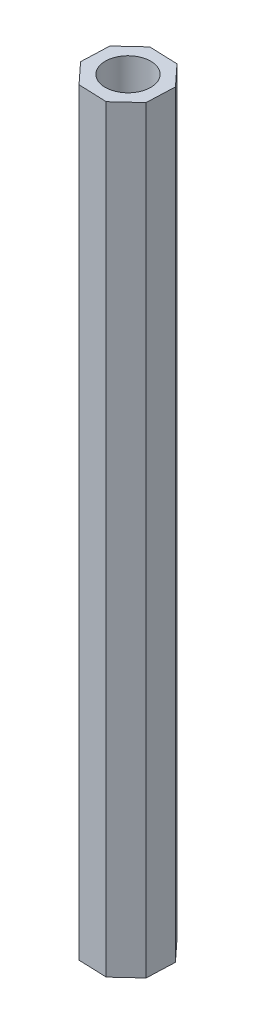
SolidWorks part; units mm, degrees
ref_plane "Front Plane" through (0, 0, 0) normal (0, 0, 1) x (1, 0, 0)
ref_plane "Top Plane" through (0, 0, 0) normal (0, 1, 0) x (1, 0, 0)
ref_plane "Right Plane" through (0, 0, 0) normal (1, 0, 0) x (0, 0, -1)
sketch "Sketch1" plane through (0, 0, 0) normal (0, 1, 0) x (1, 0, 0)
  line L1 (2.2842, 0.8447) -> (1.0179, 2.2125)
  line L2 (1.0179, 2.2125) -> (-0.8447, 2.2842)
  line L3 (-0.8447, 2.2842) -> (-2.2125, 1.0179)
  line L4 (-2.2125, 1.0179) -> (-2.2842, -0.8447)
  line L5 (-2.2842, -0.8447) -> (-1.0179, -2.2125)
  line L6 (-1.0179, -2.2125) -> (0.8447, -2.2842)
  line L7 (0.8447, -2.2842) -> (2.2125, -1.0179)
  line L8 (2.2125, -1.0179) -> (2.2842, 0.8447)
  circle A0 centre (0, 0) radius 2.25 construction
  circle A1 centre (0, 0) radius 1.5
  dimension "D2" = 3
  dimension "D1" = 4.5
extrude "Boss-Extrude1" add sketch "Sketch1" along normal blind 50
